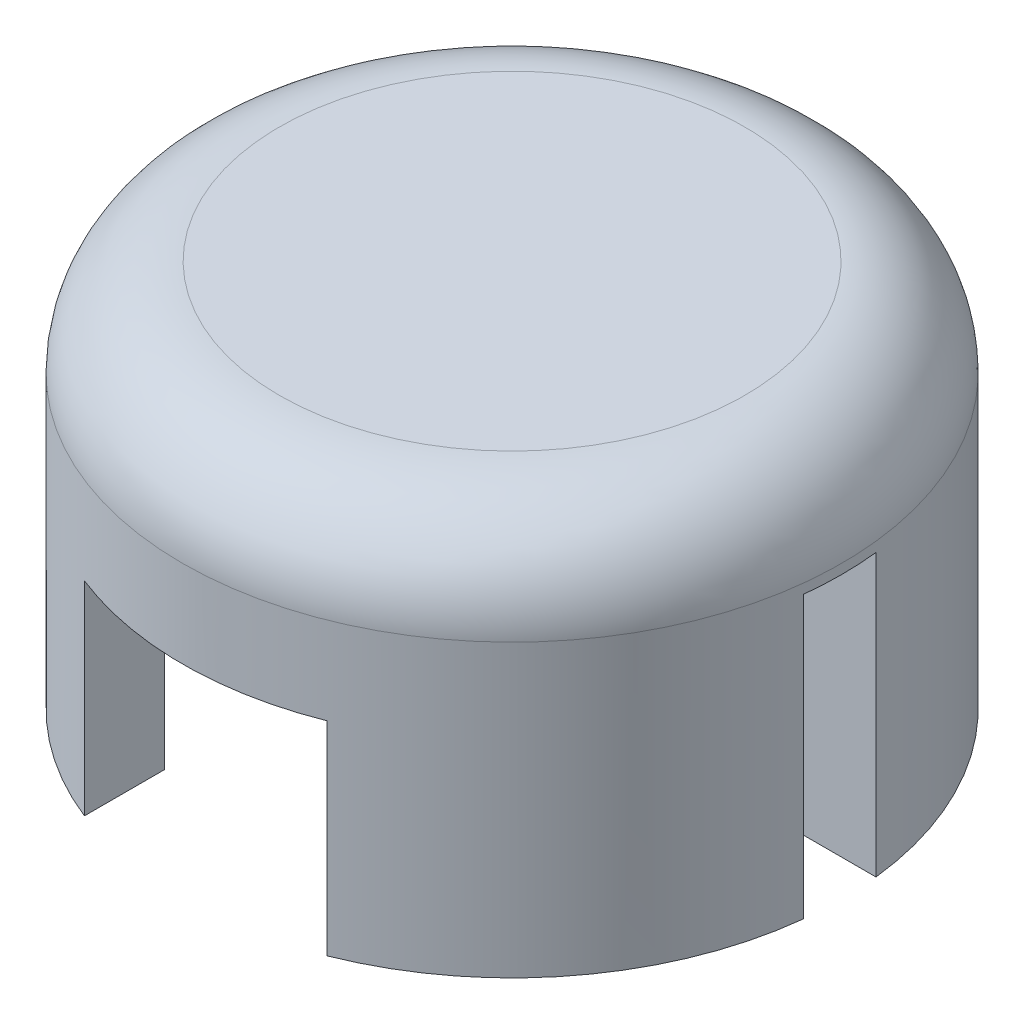
SolidWorks part; units mm, degrees
ref_plane "Front Plane" through (0, 0, 0) normal (0, 0, 1) x (1, 0, 0)
ref_plane "Top Plane" through (0, 0, 0) normal (0, 1, 0) x (1, 0, 0)
ref_plane "Right Plane" through (0, 0, 0) normal (1, 0, 0) x (0, 0, -1)
sketch "Sketch1" plane through (0, 0, 0) normal (0, 1, 0) x (1, 0, 0)
  circle A0 centre (0, 0) radius 6.8
  circle A1 centre (0, 0) radius 5.3
  dimension "D1" = 13.6
  dimension "D2" = 10.6
extrude "Boss-Extrude1" add sketch "Sketch1" along normal blind 5.8
sketch "Sketch2" plane through (0, 5.8, 0) normal (0, 1, 0) x (1, 0, 0)
  circle A0 centre (0, 0) radius 6.8
  dimension "D1" = 13.6
extrude "Boss-Extrude2" add sketch "Sketch2" along normal blind 2.2
fillet "Fillet1" radius 2 1 edges at (0, 8, 6.8)
sketch "Sketch4" plane through (0, 0, 0) normal (0, 0, 1) x (1, 0, 0)
  line L0 (0, 0) -> (2.5, 0) construction
  line L1 (-5.3, 0) -> (5.3, 0) construction
  line L3 (2.5, 0) -> (-2.5, 0)
  line L4 (2.5, 0) -> (2.5, 4.2)
  line L5 (2.5, 4.2) -> (-2.5, 4.2)
  line L6 (-2.5, 0) -> (-2.5, 4.2)
  dimension "D1" = 2.5
  dimension "D2" = 4.2
  dimension "D3" = 5
extrude "Cut-Extrude1" cut sketch "Sketch4" along normal through all
sketch "Sketch5" plane through (0, 0, 0) normal (1, 0, 0) x (0, 0, -1)
  line L0 (0, 0) -> (-0.75, 0) construction
  line L1 (-4.6733, 0) -> (5.3, 0) construction
  line L3 (-0.75, 0) -> (0.75, 0)
  line L4 (-0.75, 0) -> (-0.75, 5.8)
  line L5 (-0.75, 5.8) -> (0.75, 5.8)
  line L6 (0.75, 0) -> (0.75, 5.8)
  dimension "D1" = 0.75
  dimension "D2" = 1.5
  dimension "D3" = 5.8
extrude "Cut-Extrude2" cut sketch "Sketch5" against normal through all both and the other way through all
sketch "Sketch3" plane through (0, 5.8, 0) normal (0, -1, 0) x (1, 0, 0)
  circle A0 centre (0, 0) radius 3
  dimension "D1" = 6
extrude "Boss-Extrude3" add sketch "Sketch3" along normal blind 2.5
equation "\"outer_d\" = \"inner_d\" + 3"
equation "\"D1@Sketch1\"=\"outer_d\""
equation "\"inner_d\"= 10.6mm"
equation "\"height\" = 5.8mm"
equation "\"protrusion\" = 2.5mm"
equation "\"opening\" = 5mm"
equation "\"D2@Sketch1\"=\"inner_d\""
equation "\"D1@Boss-Extrude1\"=\"height\""
equation "\"D1@Sketch2\"=\"outer_d\""
equation "\"protusion_d\" = 6mm"
equation "\"D1@Sketch3\"=\"protusion_d\""
equation "\"D1@Boss-Extrude3\"=\"protrusion\""
equation "\"opening_height\"= 4.2mm"
equation "\"D1@Sketch4\"=\"opening\"/2"
equation "\"D2@Sketch4\"=\"opening_height\""
equation "\"D3@Sketch4\"=\"opening\""
equation "\"sym_opening_dis\"= .75 * 2"
equation "\"sym_opening_height\"= \"height\""
equation "\"D1@Sketch5\"=\"sym_opening_dis\"/2"
equation "\"D2@Sketch5\"=\"sym_opening_dis\""
equation "\"D3@Sketch5\"=\"height\""
